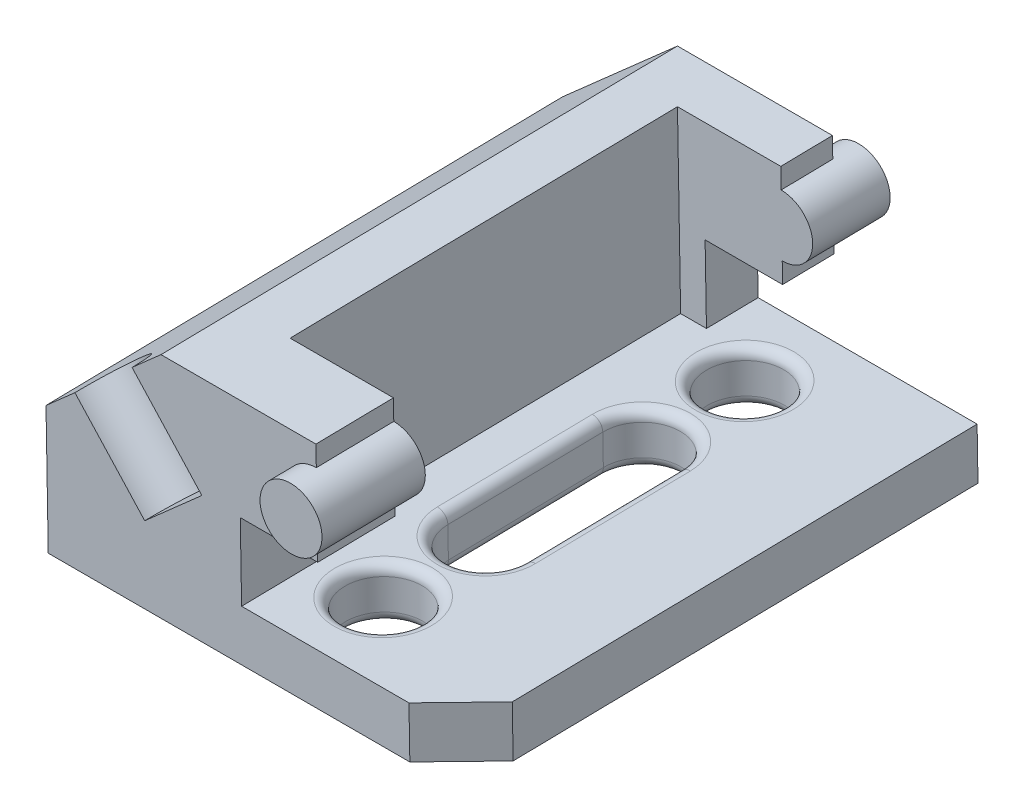
SolidWorks part; units mm, degrees
material "1060 Alloy"
ref_plane "Front Plane" through (0, 0, 0) normal (0, 0, 1) x (1, 0, 0)
ref_plane "Top Plane" through (0, 0, 0) normal (0, 1, 0) x (1, 0, 0)
ref_plane "Right Plane" through (0, 0, 0) normal (1, 0, 0) x (0, 0, -1)
sketch "Sketch2" plane through (0, 0, 0) normal (0, 1, 0) x (1, 0, 0)
  line L0 (0, 25) -> (22.6059, 45)
  line L1 (0, 0) -> (80, 0)
  line L2 (0, 0) -> (0, 10)
  line L3 (0, 10) -> (80, 10)
  line L4 (80, 0) -> (80, 10)
  line L5 (0, 10) -> (37.6059, 10)
  line L6 (0, 10) -> (0, 25)
  line L7 (0, 25) -> (37.6059, 25)
  line L8 (37.6059, 10) -> (37.6059, 25)
  line L9 (22.6059, 45) -> (52.6059, 45)
  line L10 (52.6059, 45) -> (52.6059, 25)
  line L11 (52.6059, 25) -> (37.6059, 25)
  line L12 (0, 25) -> (0, 61.0953) construction
  circle A0 centre (52.6059, 35) radius 6
  dimension "D6" = 12
  dimension "D1" = 80
  dimension "D2" = 10
  dimension "D3" = 15
  dimension "D4" = 20
  dimension "D5" = 30
  dimension "D7" = 15
  dimension "D8" = 48.5
extrude "Boss-Extrude1" add sketch "Sketch2" along normal blind 100 contours L10 A0 | L10 A0 | A0 L10 L9 L0 L7 L11 | L3 L8 L7 L6 | L1 L4 L3 L2
chamfer "Chamfer1" distance 10 angle 45 1 edges at (80, 100, -5)
sketch "Sketch3" plane through (0, 0, -45) normal (0, 0, -1) x (-1, 0, 0)
  line L0 (-22.6059, 100) -> (-22.6059, 0) construction
  line L1 (-32.6059, 10) -> (-58.6059, 10)
  line L2 (-32.6059, 10) -> (-32.6059, 85)
  line L3 (-32.6059, 85) -> (-58.6059, 85)
  line L4 (-58.6059, 10) -> (-58.6059, 85)
  line L5 (-58.6059, 100) -> (-58.6059, 0) construction
  line L6 (-22.6059, 0) -> (-52.6059, 0) construction
  dimension "D1" = 10
  dimension "D2" = 0
  dimension "D3" = 75
  dimension "D4" = 10
extrude "Cut-Extrude1" cut sketch "Sketch3" against normal up to surface (35 mm away) up to face at (61.0424, 58, -10)
sketch "Sketch4" plane through (0, 100, 0) normal (0, 1, 0) x (1, 0, 0)
  circle A0 centre (52.6059, 35) radius 6
extrude "Boss-Extrude2" add sketch "Sketch4" along normal blind 5
sketch "Sketch5" plane through (0, 0, 0) normal (0, -1, 0) x (-1, 0, 0)
  circle A0 centre (-52.6059, 35) radius 6
extrude "Boss-Extrude3" add sketch "Sketch5" along normal blind 5
sketch "Sketch6" plane through (-12.4068, 0, -14.0234) normal (-0.6626, 0, -0.749) x (-0.749, 0, 0.6626)
  line L1 (-16.5655, 100) -> (-46.7487, 100) construction
  circle A1 centre (-31.6571, 100) radius 7.5
  dimension "D1" = 15
extrude "Cut-Extrude2" cut sketch "Sketch6" against normal blind 20
sketch "Sketch7" plane through (0, 0, -10) normal (0, 0, -1) x (-1, 0, 0)
  line L0 (-50, 35) -> (-50, 65) construction
  line L1 (-57.5, 35) -> (-57.5, 65)
  line L2 (-42.5, 35) -> (-42.5, 65)
  line L3 (-80, 90) -> (-80, 0) construction
  line L5 (-37.6059, 100) -> (-70, 100) construction
  circle A0 centre (-50, 85) radius 7.5
  circle A1 centre (-50, 15) radius 7.5
  arc A2 (-57.5, 35) -> (-42.5, 35) centre (-50, 35) ccw
  arc A3 (-42.5, 65) -> (-57.5, 65) centre (-50, 65) ccw
  point P6 (-50, 50)
  dimension "D1" = 15
  dimension "D2" = 15
  dimension "D7" = 20
  dimension "D10" = 15
  dimension "D3" = 15
  dimension "D4" = 0
  dimension "D5" = 0
  dimension "D6" = 30
  dimension "D8" = 30
  dimension "D9" = 20
extrude "Cut-Extrude3" cut sketch "Sketch7" against normal through all
fillet "Fillet1" radius 2 12 edges at (42.5, 15, 0) (42.5, 15, -10) (57.5, 50, 0) (50, 27.5, 0) (50, 27.5, -10) (57.5, 50, -10) (42.5, 50, 0) (50, 72.5, 0) (50, 72.5, -10) (42.5, 50, -10) (42.5, 85, 0) (42.5, 85, -10)
move or copy body "Body-Move/Copy1" bodies to move or copy 106 copy no rotation origin (0, 50, -22.5) rotation axis (1, 0, 0) rotation angle 91
equation "\"A\"= 80"
equation "\"b\"= 75"
equation "\"C\"= 48.5"
equation "\"D1@Sketch2\"=\"A\""
equation "\"D8@Sketch2\"=\"C\""
equation "\"D3@Sketch3\"=\"b\""
